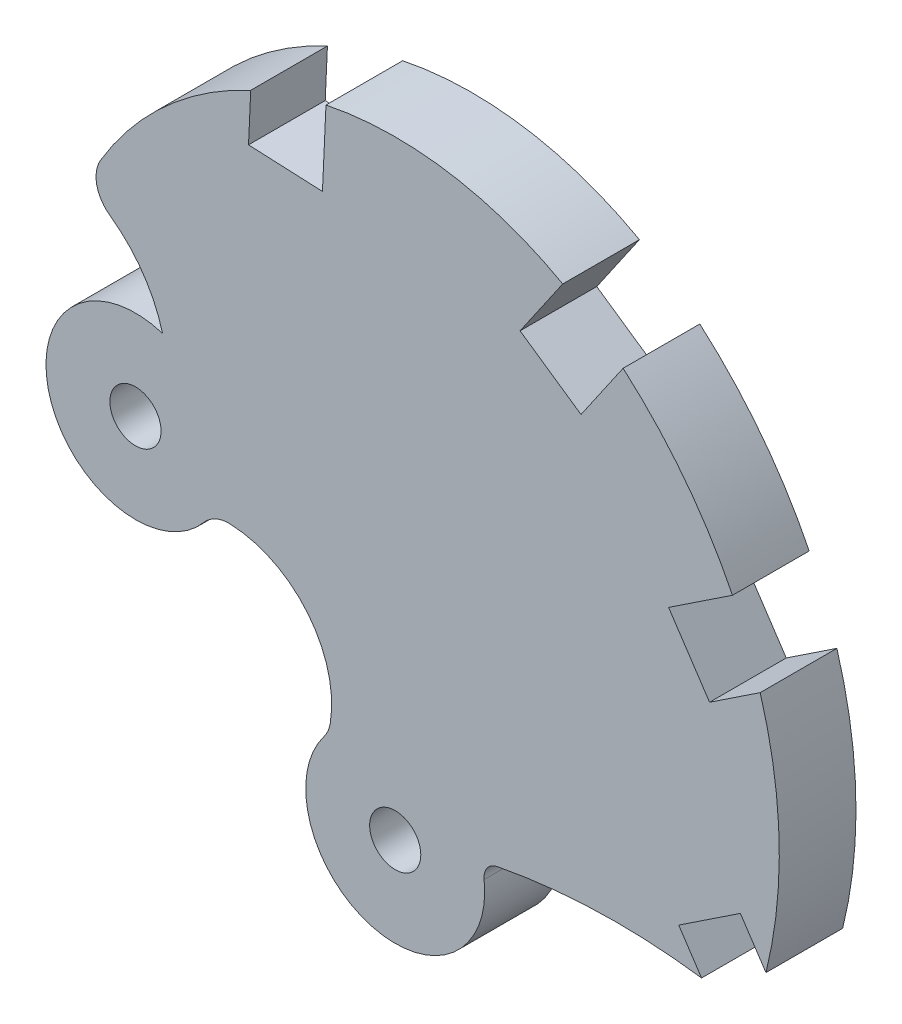
SolidWorks part; units mm, degrees
material "Acrylic (Medium-high impact)"
ref_plane "Front Plane" through (0, 0, 0) normal (0, 0, 1) x (1, 0, 0)
ref_plane "Top Plane" through (0, 0, 0) normal (0, 1, 0) x (1, 0, 0)
ref_plane "Right Plane" through (0, 0, 0) normal (1, 0, 0) x (0, 0, -1)
sketch "스케치1" plane through (0, 0, 0) normal (0, 0, 1) x (1, 0, 0)
  line L0 (7.1769, -0.3225) -> (6.6802, -1.7776) construction
  line L1 (6.6802, -1.7776) -> (6.8551, -3.3052) construction
  line L2 (2.6173, -9.1062) -> (0, -7.93) construction
  line L3 (0, -7.93) -> (-2.6173, -9.1062) construction
  line L4 (0, -7.93) -> (0, 0) construction
  line L5 (7.1769, -0.3225) -> (-7.1769, -0.3225) construction
  line L6 (7.1769, -0.3225) -> (6.8551, -3.3052) construction
  line L7 (7.1769, -0.3225) -> (-49.6435, 5.8073) construction
  line L8 (6.8551, -3.3052) -> (-49.9652, 2.8246) construction
  line L9 (-49.6435, 5.8073) -> (-49.9652, 2.8246) construction
  line L10 (-16.0371, -0.8356) -> (-49.9652, 2.8246) construction
  line L12 (0, 0) -> (0.0482, 0.4465) construction
  line L13 (0.0482, 0.4465) -> (-12.6223, 1.8134) construction
  arc A0 (-7.1769, -0.3225) -> (7.1769, -0.3225) centre (0, -80.0153) cw construction
  arc A1 (-6.8551, -3.3052) -> (6.8551, -3.3052) centre (0, -80.0153) cw construction
  circle A2 centre (-10.16, -2.153) radius 3.5 construction
  circle A3 centre (10.16, -2.153) radius 3.5 construction
  arc A4 (-10.16, -2.153) -> (10.16, -2.153) centre (0, -80.0153) cw construction
  circle A5 centre (-10.16, -2.153) radius 1
  circle A6 centre (10.16, -2.153) radius 1 construction
  circle A7 centre (0, -11.43) radius 3.5 construction
  circle A8 centre (0, -11.43) radius 1
  arc A9 (2.6173, -9.1062) -> (5.5318, -3.1984) centre (5.2764, -6.7453) cw construction
  arc A12 (5.5318, -3.1984) -> (6.8551, -3.3052) centre (0, -80.0153) cw construction
  arc A13 (7.1769, -0.3225) -> (6.8551, -3.3052) centre (10.16, -2.153) cw construction
  arc A14 (2.6173, -9.1062) -> (-2.6173, -9.1062) centre (0, -11.43) cw construction
  arc A17 (-7.1769, -0.3225) -> (-6.8551, -3.3052) centre (-10.16, -2.153) ccw construction
  arc A18 (-12.6223, 1.8134) -> (7.1769, -0.3225) centre (-4.4767, -15.5132) cw construction
  arc A20 (13.9539, -10.4604) -> (8.4608, 9.3904) centre (-2.7393, -4.3943) ccw
  arc A26 (8.4608, 9.3904) -> (-12.1291, 4.7045) centre (0.002, -1.0205) ccw
  arc A28 (-7.1781, -3.9855) -> (-2.6173, -9.1062) centre (-6.6127, -8.0734) cw
  arc A30 (3.363, -10.4604) -> (13.9539, -10.4604) centre (8.6585, -34.408) cw
  arc A31 (3.363, -10.4604) -> (-2.6173, -9.1062) centre (0, -11.43) cw
  arc A32 (-12.1291, 4.7045) -> (-9.0989, 1.1822) centre (-14.2786, -0.2093) cw
  arc A33 (-9.0989, 1.1822) -> (-7.1781, -3.9855) centre (-10.16, -2.153) ccw
  dimension "D1" = 2.5
  dimension "D2" = 2
  dimension "D3" = 11.43
  dimension "D4" = 3.556
  dimension "D7" = 57.15
  dimension "D5" = 20.32
  dimension "D6" = 3
extrude "보스-돌출1" add sketch "스케치1" along normal blind 3
sketch "스케치2" plane through (0, 0, 3) normal (0, 0, 1) x (1, 0, 0)
  line L0 (-2.5384, -8.7293) -> (13.7852, 2.1173) construction
  line L1 (12.2943, -0.6113) -> (10.6921, 1.7999)
  line L2 (12.2943, -0.6113) -> (14.7929, 1.049)
  line L3 (10.6921, 1.7999) -> (13.1907, 3.4603)
  line L4 (14.7929, 1.049) -> (13.1907, 3.4603)
  line L5 (12.2943, -0.6113) -> (13.1907, 3.4603) construction
  line L6 (10.6921, 1.7999) -> (14.7929, 1.049) construction
  line L7 (13.9539, -10.4604) -> (11.8933, -16.1866) construction
  line L12 (12.1549, -12.6857) -> (12.6584, -16.8348) construction
  line L13 (10.3254, -14.9487) -> (14.4878, -14.5718) construction
  line L14 (-3.1108, -5.89) -> (7.7758, 9.9114) construction
  line L15 (-4.9111, -4.3137) -> (-4.1758, 11.7264) construction
  line L16 (9.6959, -19.3178) -> (13.7399, -11.0197) construction
  line L17 (-5.7382, 9.2526) -> (-2.8463, 9.12)
  line L18 (-5.7382, 9.2526) -> (-5.6008, 12.2494)
  line L19 (-2.8463, 9.12) -> (-2.7089, 12.1168)
  line L20 (-5.6008, 12.2494) -> (-2.7089, 12.1168)
  line L21 (-5.7382, 9.2526) -> (-2.7089, 12.1168) construction
  line L22 (-2.8463, 9.12) -> (-5.6008, 12.2494) construction
  line L23 (4.8826, 8.2634) -> (7.2666, 6.6209)
  line L24 (4.8826, 8.2634) -> (6.5847, 10.7338)
  line L25 (7.2666, 6.6209) -> (8.9687, 9.0913)
  line L26 (6.5847, 10.7338) -> (8.9687, 9.0913)
  line L27 (4.8826, 8.2634) -> (8.9687, 9.0913) construction
  line L28 (7.2666, 6.6209) -> (6.5847, 10.7338) construction
  line L33 (13.6938, -7.7931) -> (17.6239, -6.3711) construction
  line L34 (16.3097, -9.0679) -> (15.008, -5.0963) construction
  line L35 (11.088, -8.7628) -> (13.4992, -7.1606)
  line L36 (11.088, -8.7628) -> (12.7483, -11.2615)
  line L37 (13.4992, -7.1606) -> (15.1595, -9.6593)
  line L38 (12.7483, -11.2615) -> (15.1595, -9.6593)
  line L39 (11.088, -8.7628) -> (15.1595, -9.6593) construction
  line L40 (13.4992, -7.1606) -> (12.7483, -11.2615) construction
  line L41 (13.9539, -10.4604) -> (8.1045, -1.6574) construction
  arc A0 (13.9539, -10.4604) -> (8.4608, 9.3904) centre (-2.7393, -4.3943) ccw construction
  arc A1 (8.4608, 9.3904) -> (-12.1291, 4.7045) centre (0.002, -1.0205) ccw construction
  arc A2 (8.4608, 9.3904) -> (-12.1291, 4.7045) centre (0.002, -1.0205) ccw construction
  arc A3 (-2.6173, -9.1062) -> (-7.1781, -3.9855) centre (-6.6127, -8.0734) ccw construction
  arc A5 (-2.6173, -9.1062) -> (-7.1781, -3.9855) centre (-6.6127, -8.0734) ccw construction
  point P6 (12.7425, 1.4245)
  point P7 (12.4066, -14.7602)
  point P22 (-4.2235, 10.6847)
  point P23 (6.9256, 8.6774)
  point P24 (15.6588, -7.0821)
  point P35 (13.1237, -9.2111)
  dimension "D1" = 2.895
  dimension "D2" = 3
  dimension "D3" = 3
  dimension "D4" = 2.91
  dimension "D5" = 2.91
  dimension "D6" = 3
extrude "컷-돌출1" cut sketch "스케치2" against normal up to surface (3 mm away) up to face at (-9.16, -2.153, 0)
fillet "필렛3" radius 0.635 1 edges at (3.363, -10.4604, 1.5)
fillet "필렛4" radius 1.27 1 edges at (-12.1291, 4.7045, 1.5)
fillet "필렛5" radius 1.27 2 edges at (-2.6173, -9.1062, 1.5) (-7.1781, -3.9855, 1.5)
